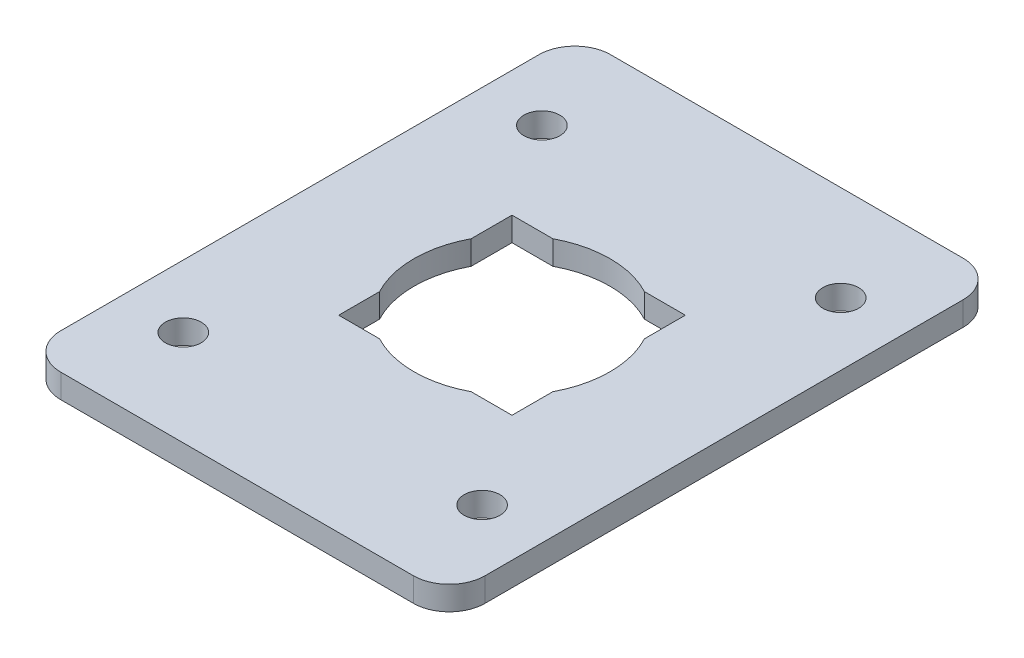
SolidWorks part; units mm, degrees
ref_plane "前视基准面" through (0, 0, 0) normal (0, 0, 1) x (1, 0, 0)
ref_plane "上视基准面" through (0, 0, 0) normal (0, 1, 0) x (1, 0, 0)
ref_plane "右视基准面" through (0, 0, 0) normal (1, 0, 0) x (0, 0, -1)
sketch "草图1" plane through (0, 0, 0) normal (0, 1, 0) x (1, 0, 0)
  line L4 (-6.3877, 3.4189) -> (-6.3877, 0)
  line L6 (-16.8877, -15.75) -> (18.6123, -15.75)
  line L7 (-16.8877, -15.75) -> (-16.8877, 30.25)
  line L8 (18.6123, -15.75) -> (18.6123, 30.25)
  line L9 (-16.8877, 30.25) -> (18.6123, 30.25)
  line L10 (-16.8877, -15.75) -> (18.6123, 30.25) construction
  line L11 (18.6123, -15.75) -> (-16.8877, 30.25) construction
  line L12 (-6.3877, 14.5) -> (-2.9688, 14.5)
  line L13 (-6.3877, 14.5) -> (-6.3877, 11.0811)
  line L14 (-6.3877, 0) -> (-2.9688, 0)
  line L15 (8.1123, 14.5) -> (8.1123, 11.0811)
  line L16 (-6.3877, 14.5) -> (8.1123, 0) construction
  line L17 (-6.3877, 0) -> (8.1123, 14.5) construction
  line L18 (8.1123, 3.4189) -> (8.1123, 0)
  line L19 (4.6934, 0) -> (8.1123, 0)
  line L20 (4.6934, 14.5) -> (8.1123, 14.5)
  arc A2 (8.1123, 3.4189) -> (8.1123, 11.0811) centre (0.8623, 7.25) ccw
  arc A3 (-2.9688, 0) -> (4.6934, 0) centre (0.8623, 7.25) ccw
  arc A4 (-6.3877, 11.0811) -> (-6.3877, 3.4189) centre (0.8623, 7.25) ccw
  arc A5 (4.6934, 14.5) -> (-2.9688, 14.5) centre (0.8623, 7.25) ccw
  point P0 (0.8623, 7.25)
  point P1 (0, 0)
  point P2 (0.8623, 7.25)
  dimension "D1" = 14.5
  dimension "D5" = 16.4
  dimension "D2" = 46
  dimension "D3" = 35.5
  dimension "D4" = 14.5
extrude "凸台-拉伸1" add sketch "草图1" along normal blind 2
fillet "圆角2" radius 3 4 edges at (18.6123, 1, 15.75) (-16.8877, 1, 15.75) (-16.8877, 1, -30.25) (18.6123, 1, -30.25)
sketch "草图2" plane through (0, 2, 0) normal (0, 1, 0) x (1, 0, 0)
  line L0 (10, -23.1319) -> (10, 23.1319)
  line L1 (10, -23.1319) -> (-10, -23.1319)
  line L2 (10, 23.1319) -> (-10, 23.1319)
  line L3 (-10, -23.1319) -> (-10, 23.1319)
  line L4 (10, -23.1319) -> (-10, 23.1319) construction
  line L5 (10, 23.1319) -> (-10, -23.1319) construction
  line L6 (12.5, -6.75) -> (12.5, 6.75)
  line L7 (-13.8877, -15.75) -> (15.6123, -15.75) construction
  line L8 (12.5, -6.75) -> (-12.5, -6.75)
  line L9 (12.5, 6.75) -> (-12.5, 6.75)
  line L10 (-12.5, -6.75) -> (-12.5, 6.75)
  line L11 (12.5, -6.75) -> (-12.5, 6.75) construction
  line L12 (12.5, 6.75) -> (-12.5, -6.75) construction
  circle A2 centre (-12.5, -6.75) radius 1.5
  circle A3 centre (-12.5, 6.75) radius 1.5
  circle A4 centre (12.5, 6.75) radius 1.5
  circle A5 centre (12.5, -6.75) radius 1.5
  point P1 (0, 0)
  point P2 (0, 0)
  dimension "D2" = 2.5
  dimension "D3" = 9
  dimension "D1" = 20
sketch "草图3" plane through (0, 0, 0) normal (0, -1, 0) x (1, 0, 0)
  line L0 (-16.8877, -7.25) -> (26.7138, -7.25) construction
  line L1 (-16.8877, -27.25) -> (-16.8877, 12.75) construction
  line L2 (0.8623, -30.25) -> (0.8623, 19.076) construction
  line L4 (15.6123, -30.25) -> (-13.8877, -30.25) construction
  circle A0 centre (-11.6377, 7.75) radius 1.5
  circle A4 centre (-11.6377, -22.25) radius 1.5
  circle A5 centre (13.3623, -22.25) radius 1.5
  circle A6 centre (13.3623, 7.75) radius 1.5
  dimension "D1" = 25
  dimension "D2" = 30
extrude "切除-拉伸1" cut sketch "草图3" against normal blind 10
